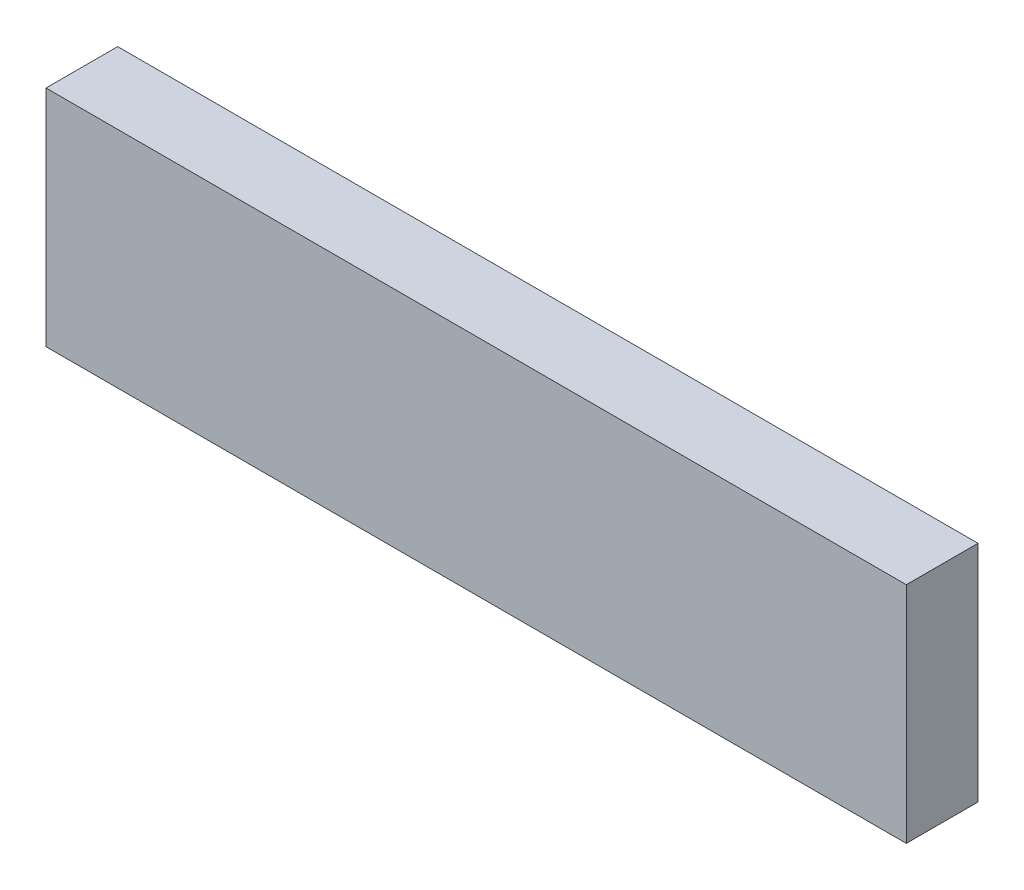
SolidWorks part; units mm, degrees
ref_plane "Front" through (0, 0, 0) normal (0, 0, 1) x (1, 0, 0)
ref_plane "Top" through (0, 0, 0) normal (0, 1, 0) x (1, 0, 0)
ref_plane "Right" through (0, 0, 0) normal (1, 0, 0) x (0, 0, -1)
sketch "Sketch1" plane through (0, 0, 0) normal (0, 1, 0) x (1, 0, 0)
  line L1 (-152.4, -12.7) -> (152.4, -12.7)
  line L2 (-152.4, -12.7) -> (-152.4, 12.7)
  line L3 (-152.4, 12.7) -> (152.4, 12.7)
  line L4 (152.4, -12.7) -> (152.4, 12.7)
  line L5 (-152.4, -12.7) -> (152.4, 12.7) construction
  line L6 (-152.4, 12.7) -> (152.4, -12.7) construction
  point P0 (0, 0)
  dimension "D1" = 304.8
  dimension "D2" = 25.4
extrude "Boss-Extrude1" add sketch "Sketch1" along normal mid plane 79.375
